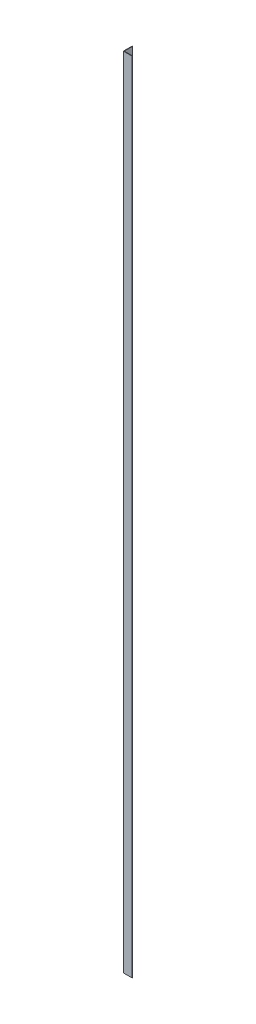
SolidWorks part; units mm, degrees
ref_plane "정면" through (0, 0, 0) normal (0, 0, 1) x (1, 0, 0)
ref_plane "윗면" through (0, 0, 0) normal (0, 1, 0) x (1, 0, 0)
ref_plane "우측면" through (0, 0, 0) normal (1, 0, 0) x (0, 0, -1)
sketch "스케치1" plane through (0, 0, 0) normal (0, 1, 0) x (1, 0, 0)
  line L1 (0, 0) -> (20, 0)
  line L2 (0, 0) -> (0, 20)
  line L3 (0, 20) -> (20, 20)
  line L4 (20, 0) -> (20, 20)
  line L5 (20, 20) -> (1, 20)
  line L6 (20, 20) -> (20, 1)
  line L7 (20, 1) -> (1, 1)
  line L8 (1, 20) -> (1, 1)
  dimension "D1" = 20
  dimension "D2" = 20
  dimension "D3" = 1
  dimension "D4" = 1
extrude "보스-돌출1" add sketch "스케치1" along normal blind 1800 contours L8 L3 L2 L1 L4 L7
